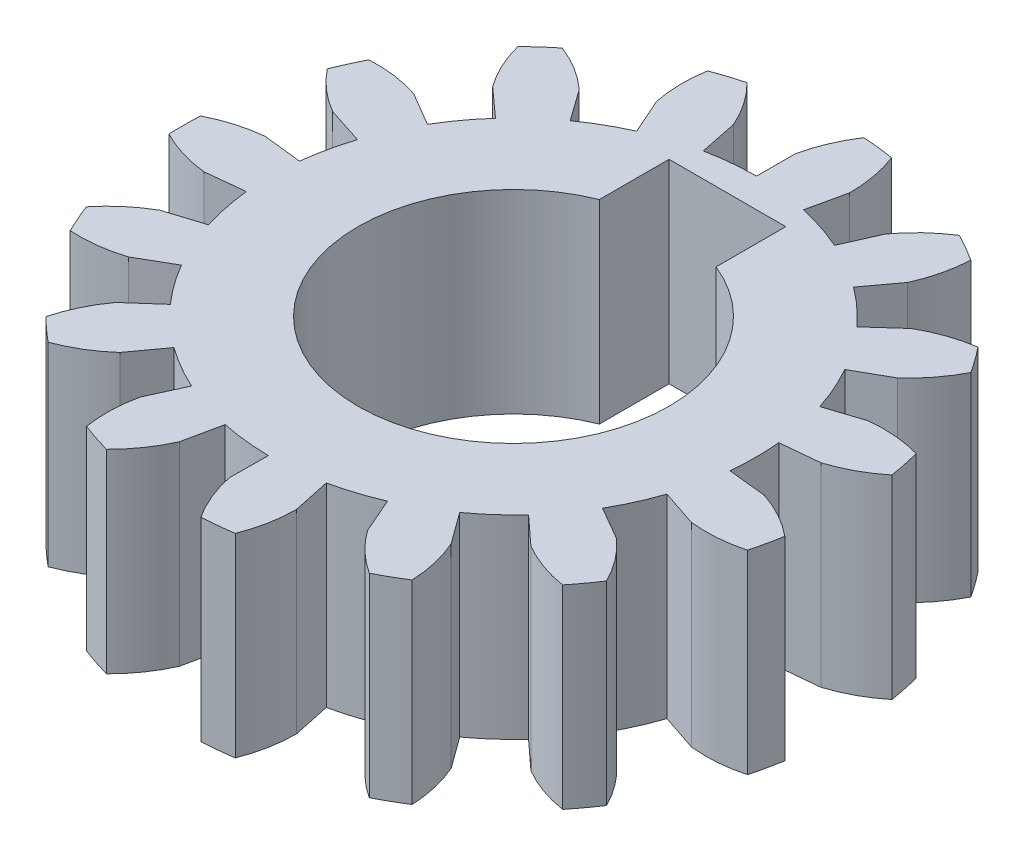
SolidWorks part; units mm, degrees
ref_plane "Front Plane" through (0, 0, 0) normal (0, 0, 1) x (1, 0, 0)
ref_plane "Top Plane" through (0, 0, 0) normal (0, 1, 0) x (1, 0, 0)
ref_plane "Right Plane" through (0, 0, 0) normal (1, 0, 0) x (0, 0, -1)
sketch "Sketch1" plane through (0, 0, 0) normal (0, 1, 0) x (1, 0, 0)
  circle A3 centre (0, 0) radius 6.25
  circle A4 centre (0, 0) radius 8.5
  circle A5 centre (0, 0) radius 7.5
  circle A6 centre (0, 0) radius 6.5
  circle A7 centre (0, 0) radius 7.2444
  dimension "pitch circle" = 15
  dimension "addendum circle" = 17
  dimension "root circle" = 12.5
  dimension "clearance circle" = 13
  dimension "base circle" = 14.4889
sketch "Sketch2" plane through (0, 0, 0) normal (0, 1, 0) x (1, 0, 0)
  line L0 (0, 0) -> (0, 7.2444)
  line L1 (0, 0) -> (3.6222, 6.2739) construction
  line L2 (0, 0) -> (6.2739, 3.6222) construction
  line L3 (0, 0) -> (7.2444, 0) construction
  line L4 (7.2444, 0) -> (7.2444, 11.3795) construction
  line L5 (6.2739, 3.6222) -> (2.4807, 10.1922) construction
  line L6 (3.6222, 6.2739) -> (0.3372, 8.1705) construction
  line L7 (0, 0) -> (3.0505, 6.8516)
  line L8 (0, 0) -> (1.5593, 7.3361) construction
  line L9 (0.8161, 7.4555) -> (0, 0) construction
  circle A0 centre (0, 0) radius 7.2444 construction
  circle A1 centre (0, 0) radius 7.5 construction
  arc A2 (1.5593, 7.3361) -> (0.0647, 7.4997) centre (0, 0) ccw
  spline S0 degree 3 poles (0, 7.2444) (0.6373, 10.2112) (4.7997, 11.3834) (7.2444, 11.3795) knots 0 0 0 0 1 1 1 1
  spline S1 degree 3 poles (1.5673, 7.0729) (1.5869, 10.1072) (-2.2234, 12.1522) (-4.611, 12.6773) knots 0 0 0 0 1 1 1 1
  point P11 (0, 0)
  dimension "Involute Control" = 90
  dimension "Base circle quarter circumference" = 11.3795
  dimension "D1" = 7.5864
  dimension "D2" = 3.7932
  dimension "pitch circle" = 24
  dimension "Involute array" = 4
sketch "Sketch3" plane through (0, 0, 0) normal (0, 1, 0) x (1, 0, 0)
  line L0 (1.5673, 7.0729) -> (1.3521, 6.102)
  line L1 (0, 0) -> (0, 7.2444) construction
  line L3 (0, 6.25) -> (0, 7.2444)
  arc A1 (0.5223, 8.4839) -> (0, 7.2444) centre (3.5325, 6.4857) ccw
  circle A2 centre (0, 0) radius 8.5 construction
  circle A3 centre (0, 0) radius 6.25 construction
  arc A7 (1.5673, 7.0729) -> (1.3255, 8.396) centre (-2.0457, 7.0963) ccw
  arc A8 (1.3521, 6.102) -> (0, 6.25) centre (0, 0) ccw
  arc A9 (1.3255, 8.396) -> (0.5223, 8.4839) centre (0, 0) ccw
  circle A10 centre (0, 0) radius 7.2444 construction
  spline S0 degree 3 poles (1.5673, 7.0729) (1.5869, 10.1072) (-2.2234, 12.1522) (-4.611, 12.6773) knots 0 0 0 0 1 1 1 1 construction
  spline S1 degree 3 poles (0, 7.2444) (0.6373, 10.2112) (4.7997, 11.3834) (7.2444, 11.3795) knots 0 0 0 0 1 1 1 1 construction
extrude "Boss-Extrude1" add sketch "Sketch3" along normal blind 5
sketch "Sketch5" plane through (0, 0, 0) normal (1, 0, 0) x (0, 0, -1)
  line L0 (0, 0) -> (0, 5.4709) construction
pattern_circular "CirPattern4" count 15 over 360 about axis through (0, 0, 0) along (0, 1, 0) of bodies 101
sketch "Sketch6" plane through (0, 0, 0) normal (0, 1, 0) x (1, 0, 0)
  circle A0 centre (0, 0) radius 6.25 construction
  circle A1 centre (0, 0) radius 6.25
extrude "Boss-Extrude2" add sketch "Sketch6" along normal up to surface (5 mm away) up to face at (-2.2305, 5, -6.967)
sketch "Sketch7" plane through (0, 5, 0) normal (0, 1, 0) x (1, 0, 0)
  line L1 (-1.5, 5.5) -> (1.5, 5.5)
  line L2 (-1.5, 5.5) -> (-1.5, 2.5)
  line L3 (-1.5, 2.5) -> (1.5, 2.5)
  line L4 (1.5, 5.5) -> (1.5, 2.5)
  line L5 (-1.5, 5.5) -> (1.5, 2.5) construction
  line L6 (-1.5, 2.5) -> (1.5, 5.5) construction
  circle A0 centre (0, 0) radius 4
  point P3 (0, 4)
  dimension "D1" = 8
  dimension "D2" = 3
extrude "Cut-Extrude1" cut sketch "Sketch7" against normal through all contours L2 A0 L4 L3 | L4 A0 L2 L3
equation "\"Module\"= 1"
equation "\"Teeth number\"= 15"
equation "\"Pressure angle\"= 15"
equation "\"pitch circle@Sketch1\"= \"Module\" * \"Teeth number\""
equation "\"addendum circle@Sketch1\"= \"pitch circle@Sketch1\" + ( \"Module\" * 2 )"
equation "\"root circle@Sketch1\"= \"pitch circle@Sketch1\" - ( ( \"Module\" * 1.25 ) * 2 )"
equation "\"clearance circle@Sketch1\"= \"pitch circle@Sketch1\" - ( \"Module\" * 2 )"
equation "\"base circle@Sketch1\"= \"pitch circle@Sketch1\" * cos ( \"Pressure angle\" )"
equation "\"D1@Sketch2\"=\"Base circle quarter circumference@Sketch2\"/3*2"
equation "\"D2@Sketch2\"=\"Base circle quarter circumference@Sketch2\"/3"
equation "\"pitch circle@Sketch2\"=360/\"Teeth number\""
equation "\"D1@CirPattern4\"=\"Teeth number\""
equation "\"Base circle quarter circumference@Sketch2\"= \"base circle@Sketch1\" * pi / 4"
